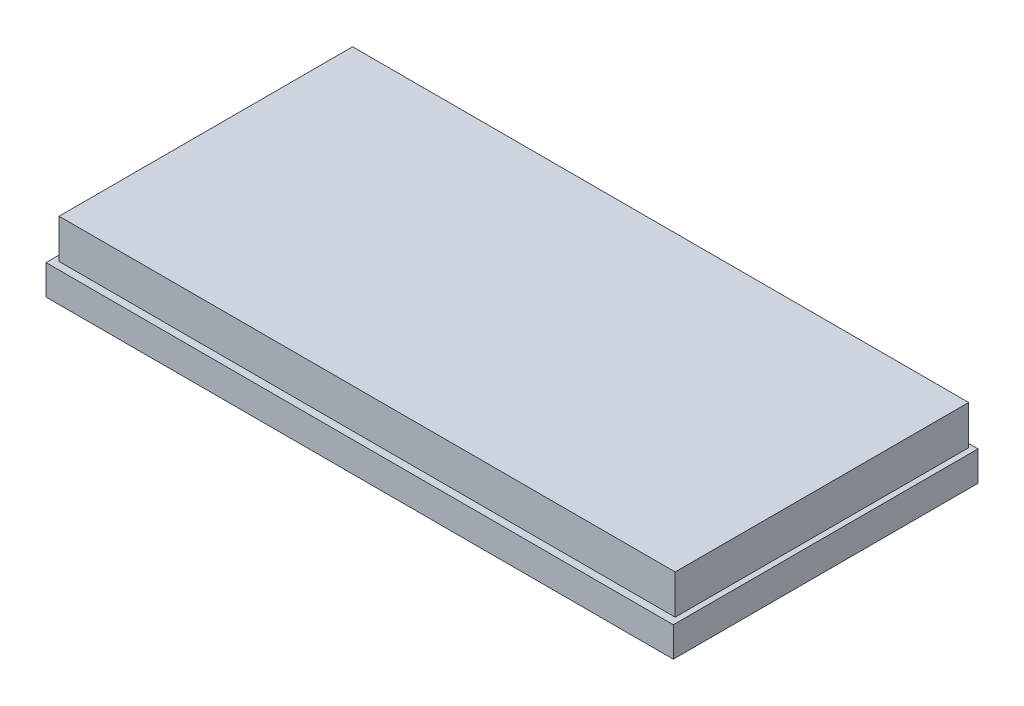
SolidWorks part; units mm, degrees
ref_plane "Front Plane" through (0, 0, 0) normal (0, 0, 1) x (1, 0, 0)
ref_plane "Top Plane" through (0, 0, 0) normal (0, 1, 0) x (1, 0, 0)
ref_plane "Right Plane" through (0, 0, 0) normal (1, 0, 0) x (0, 0, -1)
sketch "Sketch1" plane through (0, 0, 0) normal (0, 1, 0) x (1, 0, 0)
  line L1 (-82.5, -39.3) -> (82.5, -39.3)
  line L2 (-82.5, -39.3) -> (-82.5, 39.3)
  line L3 (-82.5, 39.3) -> (82.5, 39.3)
  line L4 (82.5, -39.3) -> (82.5, 39.3)
  line L5 (-82.5, -39.3) -> (82.5, 39.3) construction
  line L6 (-82.5, 39.3) -> (82.5, -39.3) construction
  point P0 (0, 0)
  dimension "D1" = 165
  dimension "D2" = 78.6
extrude "Boss-Extrude1" add sketch "Sketch1" along normal blind 10.5
sketch "Sketch2" plane through (0, 0, 0) normal (0, -1, 0) x (1, 0, 0)
  line L0 (82.5, -39.3) -> (-82.5, -39.3) construction
  line L5 (-84, 41.3) -> (84, 41.3)
  line L6 (-84, 41.3) -> (-84, -40.3)
  line L7 (-84, -40.3) -> (84, -40.3)
  line L8 (84, 41.3) -> (84, -40.3)
  point P7 (0, -40.3)
  dimension "D1" = 81.6
  dimension "D2" = 1
  dimension "D3" = 168
extrude "Boss-Extrude2" add sketch "Sketch2" along normal blind 8
